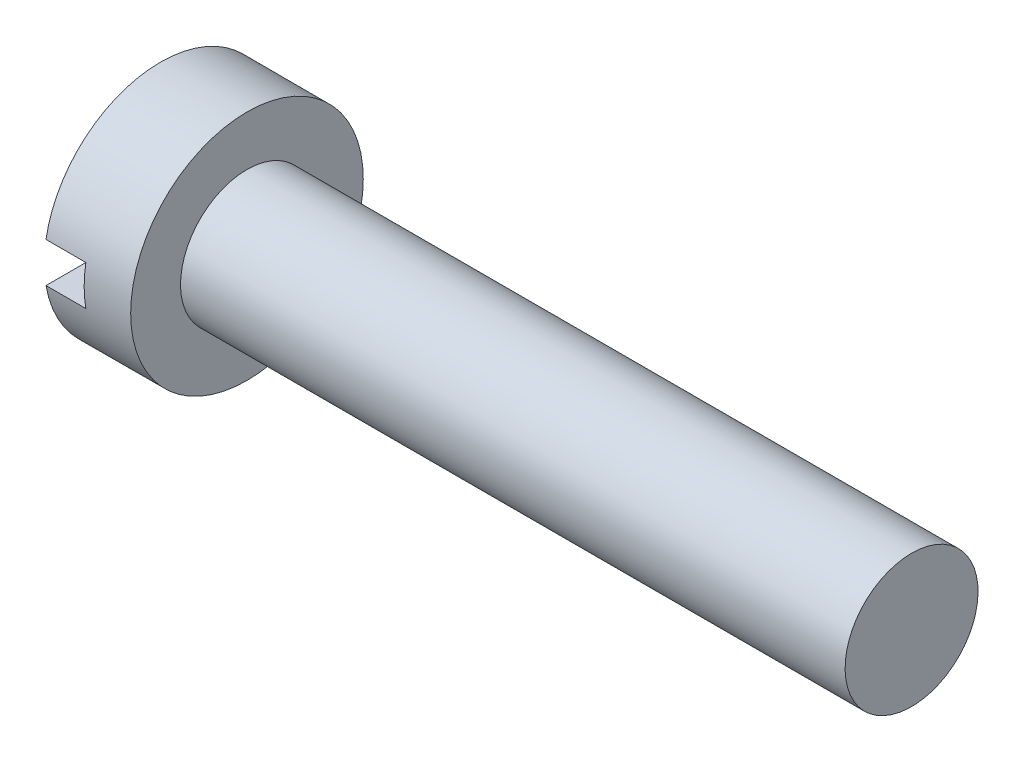
SolidWorks part; units mm, degrees
material "Plain Carbon Steel"
ref_plane "Front Plane" through (0, 0, 0) normal (0, 0, 1) x (1, 0, 0)
ref_plane "Top Plane" through (0, 0, 0) normal (0, 1, 0) x (1, 0, 0)
ref_plane "Right Plane" through (0, 0, 0) normal (1, 0, 0) x (0, 0, -1)
sketch "Sketch1" plane through (0, 0, 0) normal (0, 0, 1) x (1, 0, 0)
  line L0 (0, 0) -> (0, 3.5)
  line L1 (0, 3.5) -> (2.6, 3.5)
  line L2 (2.6, 3.5) -> (2.6, 2)
  line L3 (2.6, 2) -> (22.6, 2)
  line L4 (22.6, 2) -> (22.6, 0)
  line L5 (22.6, 0) -> (0, 0) construction
  line L6 (0, 0) -> (22.6, 0)
  dimension "D1" = 4
  dimension "D2" = 20
  dimension "D3" = 7
  dimension "D4" = 2.6
revolve "Revolve1" add sketch "Sketch1" angle 360 about L5
sketch "Sketch2" plane through (0, 0, 0) normal (-1, 0, 0) x (0, 0, 1)
  line L0 (3.5, 0) -> (-3.5, 0) construction
  line L1 (-3.5, 0.6) -> (3.5, 0.6)
  line L2 (-3.5, 0.6) -> (-3.5, -0.6)
  line L3 (-3.5, -0.6) -> (3.5, -0.6)
  line L4 (3.5, 0.6) -> (3.5, -0.6)
  circle A0 centre (0, 0) radius 3.5 construction
  dimension "D1" = 1.2
extrude "Cut-Extrude1" cut sketch "Sketch2" against normal blind 1.2
